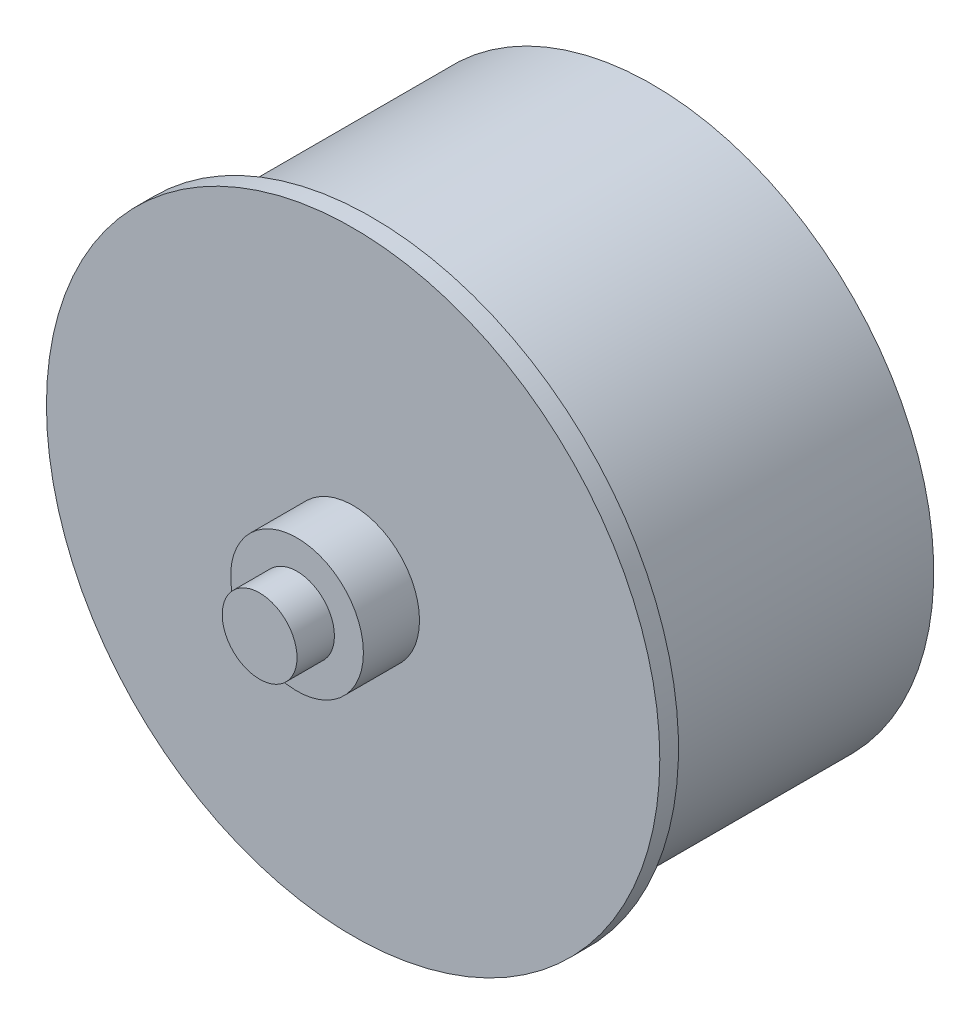
SolidWorks part; units mm, degrees
ref_plane "前视基准面" through (0, 0, 0) normal (0, 0, 1) x (1, 0, 0)
ref_plane "上视基准面" through (0, 0, 0) normal (0, 1, 0) x (1, 0, 0)
ref_plane "右视基准面" through (0, 0, 0) normal (1, 0, 0) x (0, 0, -1)
other "Configuration Table"
sketch "草图1" plane through (0, 0, 0) normal (0, 0, 1) x (1, 0, 0)
  circle A0 centre (0, 0) radius 16.4
  dimension "D1" = 32.8
extrude "凸台-拉伸1" add sketch "草图1" along normal blind 17
sketch "草图2" plane through (0, 0, 17) normal (0, 0, 1) x (1, 0, 0)
  circle A0 centre (0, 0) radius 3.55
  dimension "D1" = 7.1
extrude "凸台-拉伸2" add sketch "草图2" along normal blind 3
sketch "草图3" plane through (0, 0, 0) normal (0, 0, -1) x (-1, 0, 0)
  circle A0 centre (0, 0) radius 10.075
  dimension "D1" = 20.15
extrude "凸台-拉伸3" add sketch "草图3" along normal blind 2 separate body
sketch "草图7" plane through (0, 0, -2) normal (0, 0, -1) x (-1, 0, 0)
  line L0 (0, 0) -> (0, 8) construction
  line L1 (0, 0) -> (8, 0) construction
  line L2 (0, 0) -> (0, -8) construction
  line L3 (0, 0) -> (-8, 0) construction
  circle A0 centre (0, 8) radius 1.05
  circle A1 centre (8, 0) radius 1.05
  circle A2 centre (0, -8) radius 1.05
  circle A3 centre (-8, 0) radius 1.05
  point P13 (0, 0)
  dimension "D1" = 4
extrude "切除-拉伸3" cut sketch "草图7" against normal blind 10 contours A0 | A1 | A2 | A3
sketch "Sketch3" plane through (0, 0, 0) normal (0, 0, -1) x (-1, 0, 0)
  circle A0 centre (0, 0) radius 15.075
  circle A1 centre (0, 0) radius 16.4
extrude "Cut-Extrude1" cut sketch "Sketch3" against normal blind 16
sketch "Sketch4" plane through (0, 0, 0) normal (0, 0, -1) x (-1, 0, 0)
  circle A0 centre (0, 0) radius 10.075
  circle A1 centre (0, 0) radius 15.075
extrude "Cut-Extrude2" cut sketch "Sketch4" against normal blind 1
sketch "Sketch5" plane through (0, 0, -2) normal (0, 0, -1) x (-1, 0, 0)
  circle A0 centre (0, 0) radius 10.075
extrude "Cut-Extrude3" cut sketch "Sketch5" against normal blind 1
sketch "Sketch6" plane through (0, 0, 20) normal (0, 0, 1) x (1, 0, 0)
  circle A0 centre (0, 0) radius 2
  dimension "D1" = 4
extrude "Boss-Extrude1" add sketch "Sketch6" along normal blind 2
sketch "Sketch7" plane through (0, 0, 1) normal (0, 0, -1) x (-1, 0, 0)
  circle A0 centre (0, 0) radius 15.05
  circle A1 centre (0, 0) radius 15.075
  dimension "D1" = 30.1
  dimension "D2" = 30.15
extrude "Cut-Extrude4" cut sketch "Sketch7" against normal up to surface (15 mm away) up to face at (-15.075, 0, 16)
